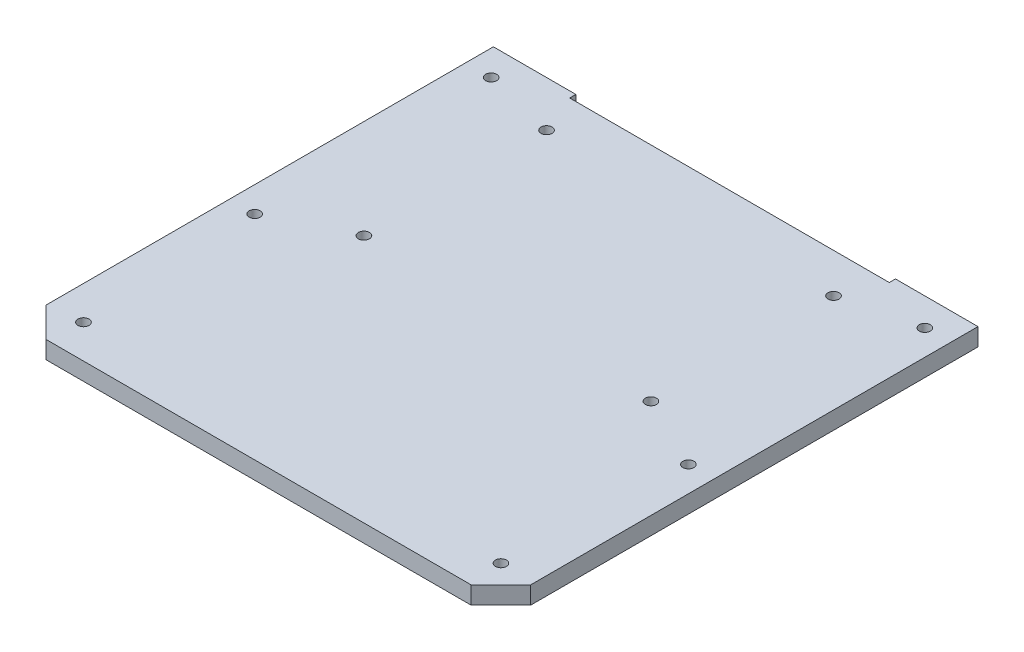
SolidWorks part; units mm, degrees
ref_plane "Front Plane" through (0, 0, 0) normal (0, 0, 1) x (1, 0, 0)
ref_plane "Top Plane" through (0, 0, 0) normal (0, 1, 0) x (1, 0, 0)
ref_plane "Right Plane" through (0, 0, 0) normal (1, 0, 0) x (0, 0, -1)
ref_plane "PZ10" through (0, 10, 0) normal (0, 1, 0) x (1, 0, 0)
sketch "Sketch1" plane through (0, 10, 0) normal (0, 1, 0) x (1, 0, 0)
  line L0 (-65.187, -156.3) -> (65.187, -156.3)
  line L1 (65.187, -156.3) -> (74.3, -147.187)
  line L2 (74.3, -147.187) -> (74.3, -11.9)
  line L3 (74.3, -11.9) -> (-74.3, -11.9)
  line L4 (-74.3, -11.9) -> (-74.3, -147.187)
  line L5 (-74.3, -147.187) -> (-65.187, -156.3)
extrude "Lid Plate" add sketch "Sketch1" along normal blind 2.4
ref_plane "PZ7" through (0, 7, 0) normal (0, 1, 0) x (1, 0, 0)
sketch "Sketch2" plane through (0, 7, 0) normal (0, 1, 0) x (1, 0, 0)
  line L0 (74.3, -11.9) -> (74.3, -147.187)
  line L1 (74.3, -147.187) -> (65.187, -156.3)
  line L2 (65.187, -156.3) -> (-65.187, -156.3)
  line L3 (-65.187, -156.3) -> (-74.3, -147.187)
  line L4 (-74.3, -147.187) -> (-74.3, -11.9)
  line L5 (-74.3, -11.9) -> (-72.7, -11.9)
  line L6 (-72.7, -11.9) -> (-72.7, -146.5243)
  line L7 (-72.7, -146.5243) -> (-64.5243, -154.7)
  line L8 (-64.5243, -154.7) -> (64.5243, -154.7)
  line L9 (64.5243, -154.7) -> (72.7, -146.5243)
  line L10 (72.7, -146.5243) -> (72.7, -11.9)
  line L11 (72.7, -11.9) -> (74.3, -11.9)
extrude "Drip Skirt" add sketch "Sketch2" along normal blind 3.01
sketch "Sketch3" plane through (0, 7, 0) normal (0, 1, 0) x (1, 0, 0)
  line L0 (-74.3, -11.9) -> (-49, -11.9)
  line L1 (-49, -11.9) -> (-49, -10)
  line L2 (-49, -10) -> (-74.3, -10)
  line L3 (-74.3, -10) -> (-74.3, -11.9)
extrude "Front Skirt L" add sketch "Sketch3" along normal blind 5.4
sketch "Sketch4" plane through (0, 7, 0) normal (0, 1, 0) x (1, 0, 0)
  line L0 (49, -11.9) -> (74.3, -11.9)
  line L1 (74.3, -11.9) -> (74.3, -10)
  line L2 (74.3, -10) -> (49, -10)
  line L3 (49, -10) -> (49, -11.9)
extrude "Front Skirt R" add sketch "Sketch4" along normal blind 5.4
ref_plane "PZ9_5" through (0, 9.5, 0) normal (0, 1, 0) x (1, 0, 0)
sketch "Sketch5" plane through (0, 9.5, 0) normal (0, 1, 0) x (1, 0, 0)
  line L0 (-40, -140) -> (23, -140)
  line L1 (23, -140) -> (23, -106)
  line L2 (23, -106) -> (-40, -106)
  line L3 (-40, -106) -> (-40, -140)
extrude "GNSS Thin Window" cut sketch "Sketch5" along normal blind 1.7
ref_plane "PZ9" through (0, 9, 0) normal (0, 1, 0) x (1, 0, 0)
sketch "Sketch6" plane through (0, 9, 0) normal (0, 1, 0) x (1, 0, 0)
  circle A0 centre (-66.5, -18.5) radius 1.7
  circle A1 centre (66.5, -18.5) radius 1.7
  circle A2 centre (-66.5, -91) radius 1.7
  circle A3 centre (66.5, -91) radius 1.7
  circle A4 centre (-64, -146) radius 1.7
  circle A5 centre (64, -146) radius 1.7
  circle A6 centre (-44, -24) radius 1.7
  circle A7 centre (-44, -80) radius 1.7
  circle A8 centre (44, -24) radius 1.7
  circle A9 centre (44, -80) radius 1.7
extrude "Screw Holes" cut sketch "Sketch6" along normal blind 4.4
equation "\"BOARD_REAR\" = 86.0"
equation "\"BOARD_FRONT\" = 41.0"
equation "\"BOARD_END\" = 22.0"
equation "\"BOARD_ANGLED\" = 30.0"
equation "\"BOARD_DEPTH\" = 41.8431"
equation "\"PCB_T\" = 1.6"
equation "\"ABOVE_PCB\" = 14.0"
equation "\"BELOW_PCB\" = 6.0"
equation "\"MID_PARTS_H\" = 9.0"
equation "\"BOARD_HOLE_PILOT\" = 1.6"
equation "\"J2_X\" = 19.0"
equation "\"DUPONT_DROP\" = 14.0"
equation "\"BEND_R\" = 5.0"
equation "\"BOARD_GAP\" = 3.0"
equation "\"TOF_FOV\" = 25.0"
equation "\"TOF_MARGIN_DEG\" = 5.0"
equation "\"TOF_WIN_MARGIN\" = 1.0"
equation "\"TOF_Z\" = 9.0"
equation "\"TOF_SIDE_BEARING\" = 90.0"
equation "\"TOF_CONE_LEN\" = 70.0"
equation "\"CAM_W\" = 29.2"
equation "\"CAM_H\" = 28.2"
equation "\"CAM_D\" = 12.35"
equation "\"CAM_FRONT_Y\" = 43.0"
equation "\"CAM_BOTTOM_Z\" = 17.0"
equation "\"CAM_LENS_UP\" = 11.6"
equation "\"CAM_LENS_OPEN\" = 9.6"
equation "\"CAM_HFOV\" = 53.5"
equation "\"CAM_VFOV\" = 41.41"
equation "\"CAM_FOV_MARGIN\" = 3.0"
equation "\"CAM_FIT\" = 0.3"
equation "\"RIBBON_W\" = 16.0"
equation "\"RIBBON_T\" = 0.3"
equation "\"RIBBON_LEN\" = 150.0"
equation "\"RIBBON_EXIT_Y\" = 35.0"
equation "\"WALL\" = 2.4"
equation "\"HEAD_X\" = 48.4"
equation "\"HEAD_REAR_Y\" = -11.9"
equation "\"CAM_FOAM\" = 2.8"
equation "\"HEAD_FRONT_Y\" = 48.2"
equation "\"HEAD_TOP_Z\" = 50.6"
equation "\"HEAD_BOT_Z\" = -28.4"
equation "\"HEAD_SPLIT_Z\" = -4.0"
equation "\"SKIRT_T\" = 1.2"
equation "\"SKIRT_H\" = 3.0"
equation "\"SKIRT_FIT\" = 0.3"
equation "\"VISOR\" = 7.8"
equation "\"VISOR_Z\" = 40.0"
equation "\"ROOF_SLOPE_Y\" = 40.0"
equation "\"ROOF_CHAMFER\" = 10.0"
equation "\"REAR_CHAMFER\" = 10.0"
equation "\"CORNER_CHAMFER\" = 6.0"
equation "\"LOWER_SIDE_FACET\" = 6.0"
equation "\"LIGHTBAR_DEPTH\" = 1.0"
equation "\"HOOD_Z\" = 14.0"
equation "\"HOOD_L\" = 6.0"
equation "\"SIDE_HOOD_L\" = 4.0"
equation "\"INSERT_M3_D\" = 4.0"
equation "\"INSERT_M3_L\" = 6.0"
equation "\"M3_CLEAR\" = 3.4"
equation "\"M2_PILOT\" = 1.6"
equation "\"M25_PILOT\" = 2.2"
equation "\"BOX_X\" = 72.4"
equation "\"BOX_FRONT_Y\" = -11.9"
equation "\"BOX_REAR_Y\" = -154.4"
equation "\"BOX_BOT_Z\" = -28.4"
equation "\"BOX_TOP_Z\" = 10.0"
equation "\"LID_T\" = 2.4"
equation "\"LID_SKIRT\" = 1.6"
equation "\"LID_TONGUE_H\" = 3.0"
equation "\"LID_FIT\" = 0.3"
equation "\"GNSS_WIN_T\" = 1.2"
equation "\"DIVIDER_Y\" = -86.0"
equation "\"PI_X0\" = -40.0"
equation "\"PI_X1\" = 45.0"
equation "\"PI_Y1\" = -26.3"
equation "\"PI_Y0\" = -82.3"
equation "\"PI_STANDOFF\" = 8.0"
equation "\"ESP_X0\" = -46.0"
equation "\"ESP_Y0\" = -149.0"
equation "\"ESP_L\" = 75.0"
equation "\"ESP_W\" = 52.0"
equation "\"ESP_STANDOFF\" = 12.0"
equation "\"BOX_REAR_CHAMFER\" = 8.0"
equation "\"BOX_REAR_FACET\" = 4.0"
equation "\"VENT_UPSTAND\" = 3.0"
equation "\"TUBE_D\" = 22.2"
equation "\"TUBE_LINER\" = 1.0"
equation "\"MOUNT_Y\" = -70.0"
equation "\"RAIL_W\" = 30.0"
equation "\"RAIL_W2\" = 38.0"
equation "\"RAIL_H\" = 6.0"
equation "\"SLIDE\" = 0.3"
equation "\"STOP_T\" = 6.0"
equation "\"CLAMP_W\" = 40.0"
equation "\"CLAMP_HALF\" = 20.0"
equation "\"CLAMP_DROP\" = 12.0"
equation "\"CAP_T\" = 12.0"
equation "\"CLAMP_BOLT_OFF\" = 16.6"
equation "\"M5_INSERT_D\" = 6.4"
equation "\"M5_CLEAR\" = 5.5"
equation "\"LOCK_D\" = 3.3"
equation "\"POD_TILT_DEG\" = 0.0"
equation "\"PRINT_LIMIT\" = 180.0"
